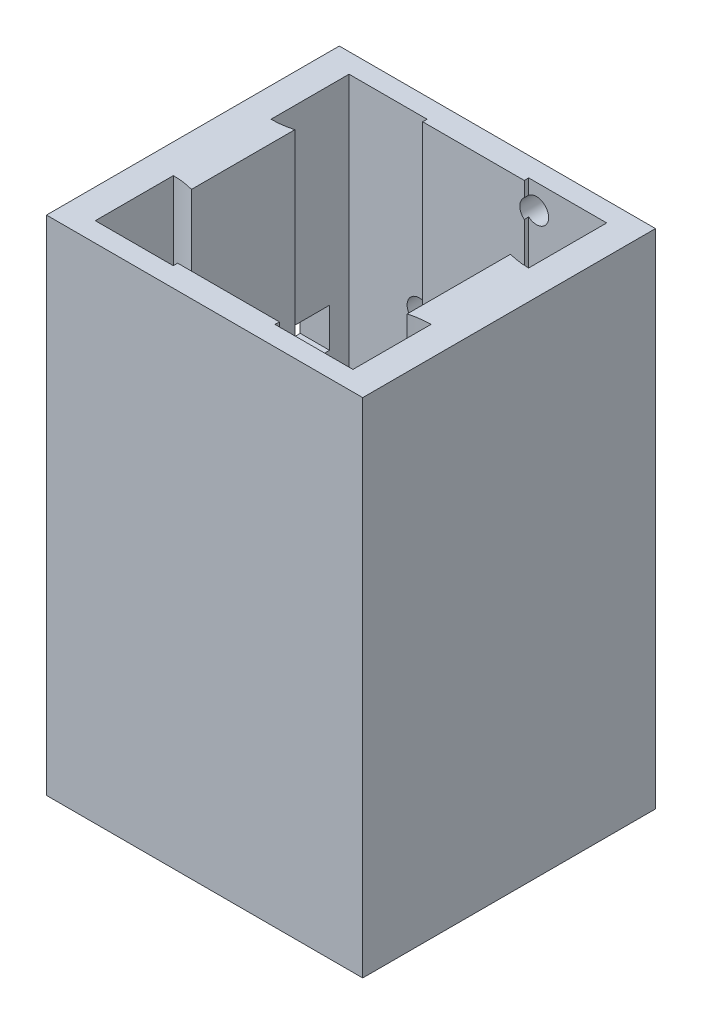
SolidWorks part; units mm, degrees
ref_plane "Front Plane" through (0, 0, 0) normal (0, 0, 1) x (1, 0, 0)
ref_plane "Top Plane" through (0, 0, 0) normal (0, 1, 0) x (1, 0, 0)
ref_plane "Right Plane" through (0, 0, 0) normal (1, 0, 0) x (0, 0, -1)
sketch "Sketch1" plane through (0, 0, 0) normal (0, 1, 0) x (1, 0, 0)
  line L0 (16.2, 0) -> (16.2, -30) construction
  line L1 (0, 0) -> (32.4, 0)
  line L2 (0, 0) -> (0, -30)
  line L3 (0, -30) -> (32.4, -30)
  line L4 (32.4, 0) -> (32.4, -30)
  line L5 (0, -15) -> (32.4, -15) construction
  circle A0 centre (6.2, -5) radius 1.75
  circle A1 centre (26.2, -5) radius 1.75
  circle A2 centre (26.2, -25) radius 1.75
  circle A3 centre (6.2, -25) radius 1.75
  dimension "D3" = 3.5
  dimension "D8" = 20
  dimension "D1" = 30
  dimension "D2" = 32.4
  dimension "D6" = 10
  dimension "D7" = 10
  dimension "D9" = 20
  dimension "D4" = 2
  dimension "D5" = 2
extrude "Boss-Extrude1" add sketch "Sketch1" along normal blind 25
sketch "Sketch2" plane through (0, 25, 0) normal (0, 1, 0) x (1, 0, 0)
  line L1 (16.2, 0) -> (16.2, -30) construction
  line L2 (32.4, 0) -> (0, 0) construction
  line L3 (0, -30) -> (32.4, -30) construction
  line L4 (0, -15) -> (32.4, -15) construction
  line L5 (0, 0) -> (0, -30) construction
  line L6 (32.4, -30) -> (32.4, 0) construction
  circle A0 centre (16.2, -15) radius 4
  point P14 (18.7071, -16.8704)
  dimension "D1" = 8
extrude "Cut-Extrude1" cut sketch "Sketch2" against normal blind 20
sketch "Sketch3" plane through (0, 25, 0) normal (0, 1, 0) x (1, 0, 0)
  line L0 (3, -10) -> (3, -20)
  line L1 (0, 0) -> (32.4, 0)
  line L2 (0, 0) -> (0, -30)
  line L3 (0, -30) -> (32.4, -30)
  line L4 (32.4, 0) -> (32.4, -30)
  line L5 (3, -2) -> (29.4, -2)
  line L6 (3, -2) -> (3, -28)
  line L7 (3, -28) -> (29.4, -28)
  line L8 (29.4, -2) -> (29.4, -28)
  line L9 (11, -28) -> (21.4, -28)
  line L10 (29.4, -20) -> (29.4, -10)
  line L11 (21.4, -2) -> (11, -2)
  arc A0 (11, -2) -> (3, -10) centre (3, -2) cw
  arc A1 (21.4, -28) -> (29.4, -20) centre (29.4, -28) cw
  arc A2 (29.4, -10) -> (21.4, -2) centre (29.4, -2) cw
  arc A3 (3, -20) -> (11, -28) centre (3, -28) cw
  circle M17 centre (16.2, -15) radius 4
  line M20 (0, 0) -> (0, -30)
  line M21 (0, -30) -> (32.4, -30)
  line M22 (32.4, -30) -> (32.4, 0)
  line M23 (32.4, 0) -> (0, 0)
  dimension "D5" = 8
  dimension "D6" = 8
  dimension "D7" = 8
  dimension "D8" = 8
  dimension "D1" = 3
  dimension "D2" = 3
  dimension "D3" = 2
  dimension "D4" = 2
extrude "Boss-Extrude2" add sketch "Sketch3" along normal blind 3 contours L5 L8 L7 L6 L0 M23 M20 M21 M22 | L0 A3 L7 A1 L8 A2 L5 A0 M17 | L2 L1 L4 L3
sketch "Sketch4" plane through (0, 28, 0) normal (0, 1, 0) x (1, 0, 0)
  line L0 (16.2, 0) -> (16.2, -30) construction
  line L9 (32.4, 0) -> (0, 0) construction
  line L10 (0, -30) -> (32.4, -30) construction
  line L11 (32.4, -15) -> (0, -15) construction
  line L12 (5.15, -20.2943) -> (5.15, -9.7057)
  line L13 (0, 0) -> (0, -30) construction
  line L14 (32.4, -30) -> (32.4, 0) construction
  line L15 (29.4, -20) -> (29.4, -28) construction
  line L16 (21.4, -28) -> (29.4, -28) construction
  line L17 (3, -28) -> (11, -28) construction
  line L18 (3, -20) -> (3, -28) construction
  line L19 (3, -2) -> (11, -2) construction
  line L20 (21.4, -2) -> (29.4, -2) construction
  line L21 (29.4, -2) -> (29.4, -10) construction
  line L22 (3, -2) -> (3, -10) construction
  line L23 (0, -30) -> (32.4, -30)
  line L24 (0, 0) -> (0, -30)
  line L25 (32.4, 0) -> (0, 0)
  line L26 (32.4, -30) -> (32.4, 0)
  line L27 (29.4, -20) -> (29.4, -28)
  line L28 (21.4, -28) -> (29.4, -28)
  line L29 (3, -28) -> (11, -28)
  line L30 (3, -20) -> (3, -28)
  line L31 (3, -2) -> (11, -2)
  line L32 (21.4, -2) -> (29.4, -2)
  line L33 (29.4, -2) -> (29.4, -10)
  line L34 (3, -2) -> (3, -10)
  line L35 (10.9873, -2.45) -> (21.4127, -2.45)
  line L36 (27.25, -9.7057) -> (27.25, -20.2943)
  line L37 (10.9873, -27.55) -> (21.4127, -27.55)
  arc A0 (29.4, -20) -> (21.4, -28) centre (29.4, -28) ccw construction
  arc A1 (11, -28) -> (3, -20) centre (3, -28) ccw construction
  arc A2 (21.4, -2) -> (29.4, -10) centre (29.4, -2) ccw construction
  arc A3 (3, -10) -> (11, -2) centre (3, -2) ccw construction
  arc A4 (29.4, -20) -> (27.25, -20.2943) centre (29.4, -28) ccw
  arc A5 (11, -28) -> (10.9873, -27.55) centre (3, -28) ccw
  arc A6 (21.4, -2) -> (21.4127, -2.45) centre (29.4, -2) ccw
  arc A7 (3, -10) -> (5.15, -9.7057) centre (3, -2) ccw
  arc A8 (10.9873, -2.45) -> (11, -2) centre (3, -2) ccw
  arc A9 (5.15, -20.2943) -> (3, -20) centre (3, -28) ccw
  arc A10 (21.4127, -27.55) -> (21.4, -28) centre (29.4, -28) ccw
  arc A11 (27.25, -9.7057) -> (29.4, -10) centre (29.4, -2) ccw
  point P15 (16.2, -15)
  dimension "D1" = 22.1
  dimension "D2" = 11.05
  dimension "D3" = 25.1
  dimension "D4" = 12.55
extrude "Boss-Extrude3" add sketch "Sketch4" along normal blind 23.5
sketch "Sketch5" plane through (0, 0, 0) normal (0, 0, -1) x (-1, 0, 0)
  line L0 (-32.4, 28) -> (0, 28) construction
  line L1 (-32.4, 28) -> (0, 28)
  line L2 (-5.15, 28) -> (-5.15, 36.9803) construction
  line L3 (0, 51.5) -> (0, 0) construction
  line L4 (-27.25, 28) -> (-27.25, 39.4314) construction
  line L5 (-32.4, 51.5) -> (-32.4, 0) construction
  line L6 (-16.2, 28) -> (-16.2, 36.5707) construction
  circle A0 centre (-22.2, 49) radius 1.25
  circle A1 centre (-10.2, 34) radius 1.25
  dimension "D6" = 2.5
  dimension "D7" = 2.5
  dimension "D1" = 6
  dimension "D2" = 12
  dimension "D3" = 5.15
  dimension "D4" = 5.15
  dimension "D5" = 6
  dimension "D8" = 15
extrude "Cut-Extrude2" cut sketch "Sketch5" along direction (0, 0, 1) on the side against the normal up to surface (2.45 mm away) contours A0 | A1
sketch "Sketch6" plane through (0, 0, 0) normal (-1, 0, 0) x (0, 0, 1)
  line L0 (0, 28) -> (30, 28) construction
  line L1 (0, 28) -> (30, 28)
  line L2 (0, 51.5) -> (0, 0) construction
  line L3 (4, 28) -> (26, 28)
  line L4 (4, 28) -> (4, 32)
  line L5 (4, 32) -> (26, 32)
  line L6 (26, 28) -> (26, 32)
  line L7 (30, 51.5) -> (30, 0) construction
  dimension "D1" = 4
  dimension "D2" = 4
  dimension "D3" = 4
extrude "Cut-Extrude3" cut sketch "Sketch6" along direction (1, 0, 0) on the side against the normal up to surface (5.15 mm away) contours L1 L6 L5 L4
